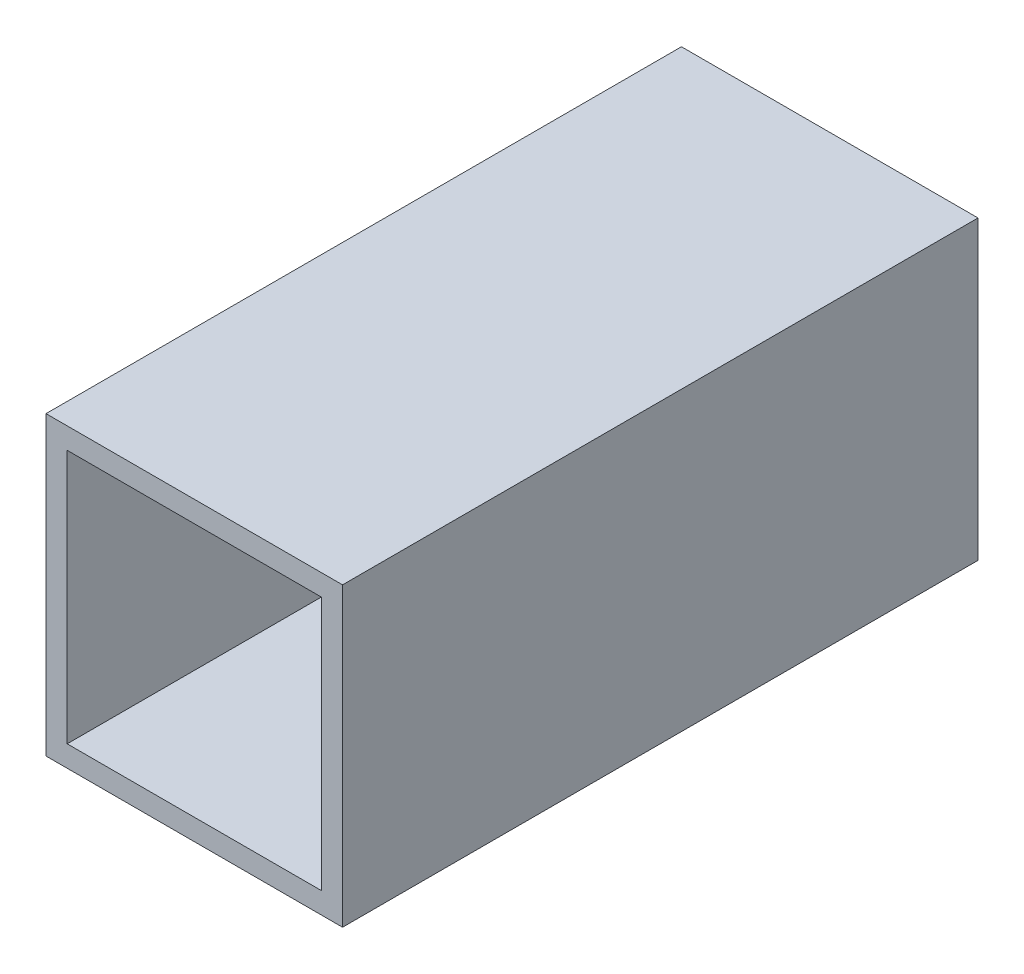
SolidWorks part; units mm, degrees
ref_plane "Front Plane" through (0, 0, 0) normal (0, 0, 1) x (1, 0, 0)
ref_plane "Top Plane" through (0, 0, 0) normal (0, 1, 0) x (1, 0, 0)
ref_plane "Right Plane" through (0, 0, 0) normal (1, 0, 0) x (0, 0, -1)
sketch "Sketch2" plane through (0, 0, 0) normal (0, 0, 1) x (1, 0, 0)
  line L1 (-22.225, 22.225) -> (22.225, 22.225)
  line L2 (-22.225, 22.225) -> (-22.225, -22.225)
  line L3 (-22.225, -22.225) -> (22.225, -22.225)
  line L4 (22.225, 22.225) -> (22.225, -22.225)
  line L5 (-22.225, 22.225) -> (22.225, -22.225) construction
  line L6 (-22.225, -22.225) -> (22.225, 22.225) construction
  line L7 (-19.05, 19.05) -> (19.05, 19.05)
  line L8 (-19.05, 19.05) -> (-19.05, -19.05)
  line L9 (-19.05, -19.05) -> (19.05, -19.05)
  line L10 (19.05, 19.05) -> (19.05, -19.05)
  line L11 (-19.05, 19.05) -> (19.05, -19.05) construction
  line L12 (-19.05, -19.05) -> (19.05, 19.05) construction
  point P0 (0, 0)
  point P6 (0, 0)
  dimension "D1" = 44.45
  dimension "D2" = 44.45
  dimension "D3" = 38.1
  dimension "D4" = 38.1
extrude "Boss-Extrude1" add sketch "Sketch2" along normal blind 95.25
